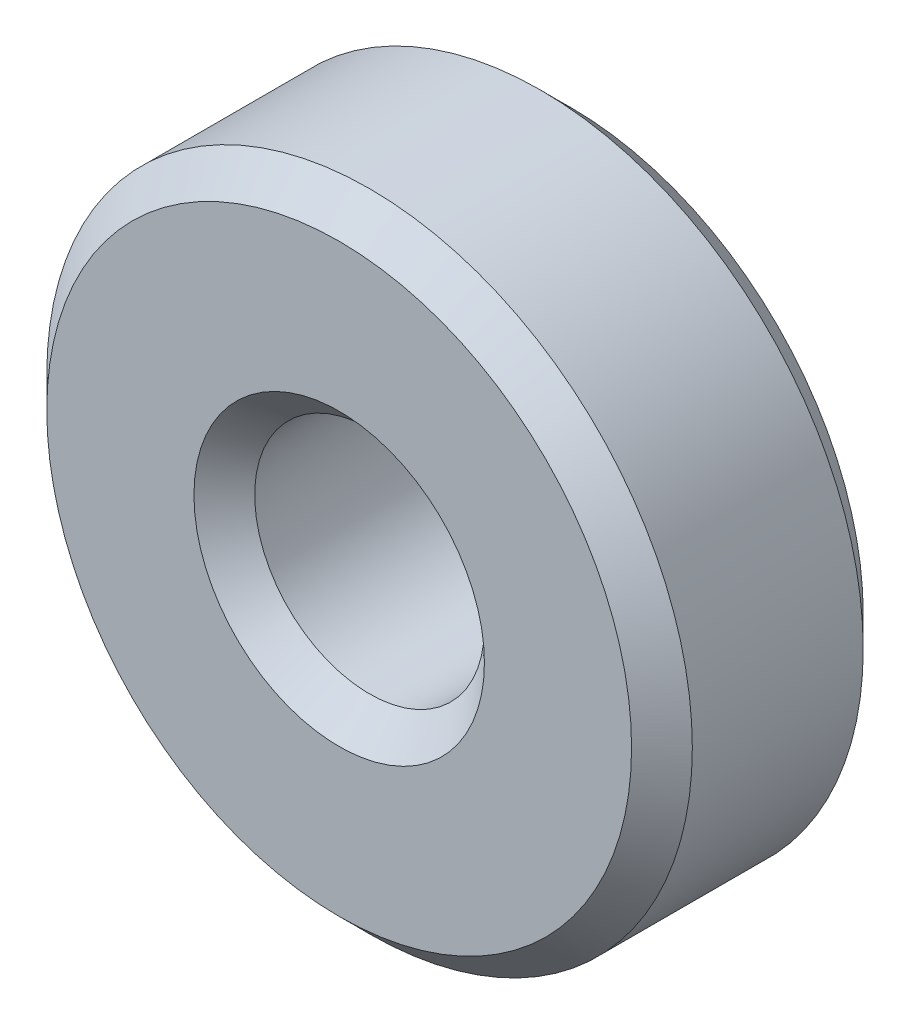
SolidWorks part; units mm, degrees
material "1023 Carbon Steel Sheet (SS)"
ref_plane "Front Plane" through (0, 0, 0) normal (0, 0, 1) x (1, 0, 0)
ref_plane "Top Plane" through (0, 0, 0) normal (0, 1, 0) x (1, 0, 0)
ref_plane "Right Plane" through (0, 0, 0) normal (1, 0, 0) x (0, 0, -1)
sketch "Sketch1" plane through (0, 0, 0) normal (0, 0, 1) x (1, 0, 0)
  circle A0 centre (0, 0) radius 3.025
  circle A1 centre (0, 0) radius 8.5
  dimension "D1" = 6.05
  dimension "D2" = 17
extrude "Boss-Extrude1" add sketch "Sketch1" along normal mid plane 6.1
chamfer "Chamfer1" distance 0.8 angle 45 4 edges at (3.025, 0, -3.05) (3.025, 0, 3.05) (8.5, 0, -3.05) (8.5, 0, 3.05)
